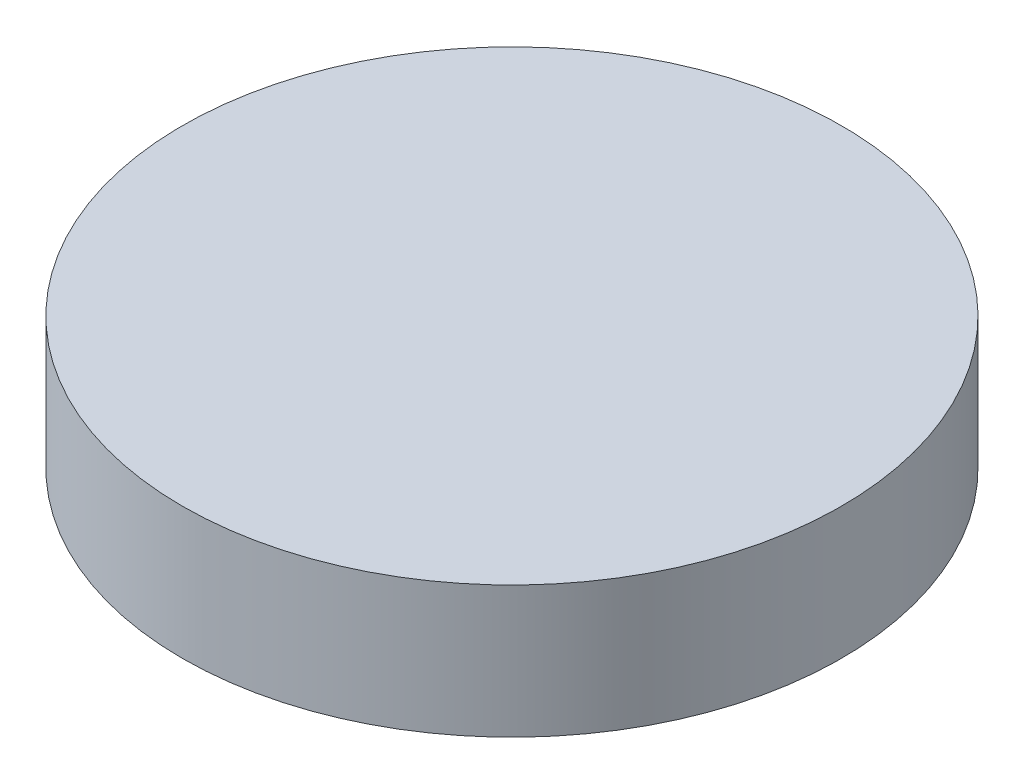
SolidWorks part; units mm, degrees
material "Brass"
ref_plane "Front Plane" through (0, 0, 0) normal (0, 0, 1) x (1, 0, 0)
ref_plane "Top Plane" through (0, 0, 0) normal (0, 1, 0) x (1, 0, 0)
ref_plane "Right Plane" through (0, 0, 0) normal (1, 0, 0) x (0, 0, -1)
sketch "Sketch1" plane through (0, 0, 0) normal (0, 1, 0) x (1, 0, 0)
  circle A0 centre (0, 0) radius 10
  dimension "D1" = 20
extrude "Boss-Extrude1" add sketch "Sketch1" along normal blind 4
